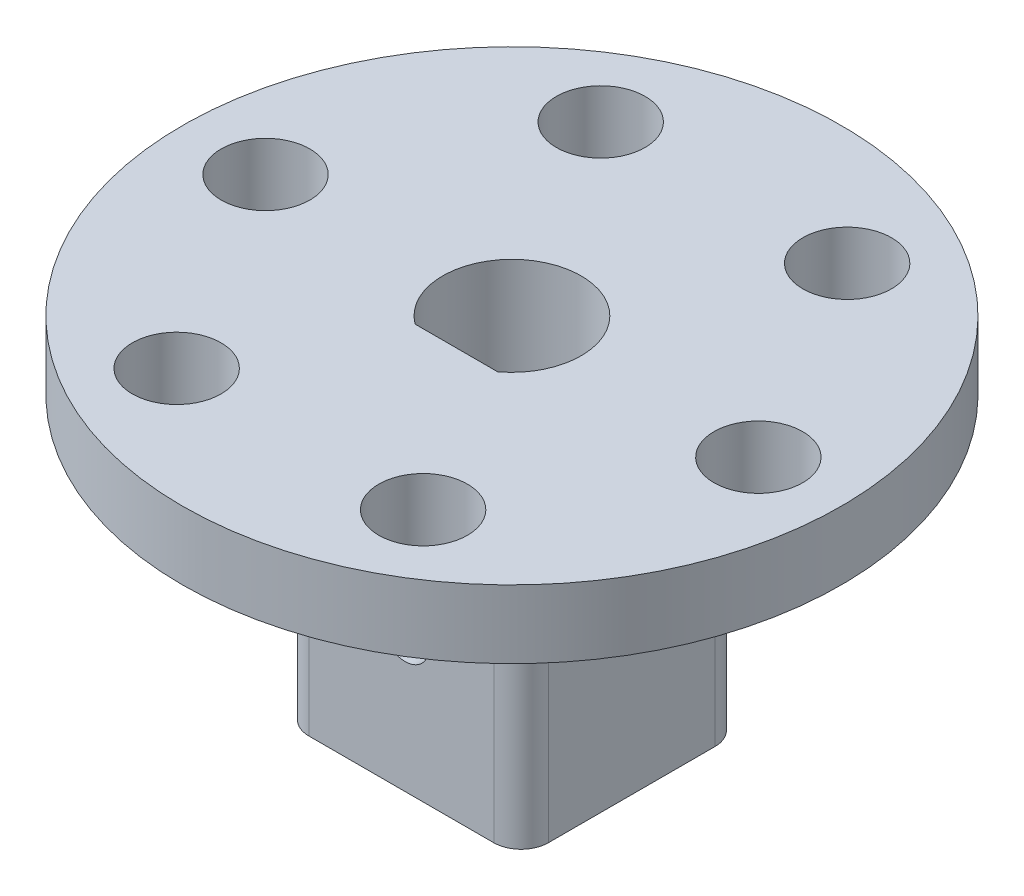
SolidWorks part; units mm, degrees
ref_plane "前视基准面" through (0, 0, 0) normal (0, 0, 1) x (1, 0, 0)
ref_plane "上视基准面" through (0, 0, 0) normal (0, 1, 0) x (1, 0, 0)
ref_plane "右视基准面" through (0, 0, 0) normal (1, 0, 0) x (0, 0, -1)
sketch "草图1" plane through (0, 0, 0) normal (0, 1, 0) x (1, 0, 0)
  line L7 (-10.75, -10.75) -> (10.75, -10.75)
  line L8 (-10.75, -10.75) -> (-10.75, 10.75)
  line L9 (-10.75, 10.75) -> (10.75, 10.75)
  line L10 (10.75, -10.75) -> (10.75, 10.75)
  line L11 (-10.75, -10.75) -> (10.75, 10.75) construction
  line L12 (-10.75, 10.75) -> (10.75, -10.75) construction
  line L13 (-15, -15) -> (15, -15)
  line L14 (-15, -15) -> (-15, 15)
  line L15 (-15, 15) -> (15, 15)
  line L16 (15, -15) -> (15, 15)
  line L17 (-15, -15) -> (15, 15) construction
  line L18 (-15, 15) -> (15, -15) construction
  point P0 (0, 0)
  point P5 (0, 0)
  dimension "D1" = 21.5
  dimension "D2" = 21.5
  dimension "D3" = 30
  dimension "D4" = 30
extrude "凸台-拉伸1" add sketch "草图1" along normal blind 5
sketch "草图2" plane through (0, 5, 0) normal (0, 1, 0) x (1, 0, 0)
  line L1 (-15, 15) -> (15, 15)
  line L2 (-15, 15) -> (-15, -15)
  line L3 (-15, -15) -> (15, -15)
  line L4 (15, 15) -> (15, -15)
extrude "凸台-拉伸2" add sketch "草图2" along normal blind 5
sketch "草图3" plane through (0, 10, 0) normal (0, 1, 0) x (1, 0, 0)
  circle A0 centre (0, 0) radius 5.5
  dimension "D1" = 11
sketch "草图4" plane through (0, 10, 0) normal (0, 1, 0) x (1, 0, 0)
  line L6 (0, 0) -> (0, -3.7936) construction
  line L7 (-8.7773, 8.1079) -> (8.7773, 8.1079)
  line L8 (-8.7773, 8.1079) -> (-8.7773, -8.1079)
  line L9 (-8.7773, -8.1079) -> (8.7773, -8.1079)
  line L10 (8.7773, 8.1079) -> (8.7773, -8.1079)
  line L11 (0, 0) -> (3.9424, 0) construction
extrude "凸台-拉伸3" add sketch "草图4" along normal blind 11
sketch "草图5" plane through (0, 21, 0) normal (0, 1, 0) x (1, 0, 0)
  line L1 (8.9491, 15.6177) -> (-9.0508, 15.559) construction
  line L2 (-9.0508, 15.559) -> (-17.9999, -0.0587) construction
  line L3 (-17.9999, -0.0587) -> (-8.9491, -15.6177) construction
  line L4 (-8.9491, -15.6177) -> (9.0508, -15.559) construction
  line L5 (9.0508, -15.559) -> (17.9999, 0.0587) construction
  line L6 (17.9999, 0.0587) -> (8.9491, 15.6177) construction
  circle A0 centre (0, 0) radius 15.5885 construction
  circle A1 centre (8.9491, 15.6177) radius 3.25
  circle A2 centre (17.9999, 0.0587) radius 3.25
  circle A3 centre (9.0508, -15.559) radius 3.25
  circle A4 centre (-8.9491, -15.6177) radius 3.25
  circle A5 centre (-17.9999, -0.0587) radius 3.25
  circle A6 centre (-9.0508, 15.559) radius 3.25
  circle A7 centre (0, 0) radius 24.1522
  dimension "D2" = 6.5
  dimension "D1" = 18
  dimension "D3" = 6
extrude "凸台-拉伸4" add sketch "草图5" along normal blind 5
sketch "草图6" plane through (0, 5, 0) normal (0, -1, 0) x (1, 0, 0)
  line L0 (-3.0249, 4.075) -> (3.0249, 4.075)
  arc A0 (-3.0249, 4.075) -> (3.0249, 4.075) centre (0, 0) ccw
  point P1 (0, -5.075)
  dimension "D1" = 10.15
  dimension "D2" = 9.15
extrude "切除-拉伸2" cut sketch "草图6" against normal up to surface (21 mm away) up to face at (-17.9999, 26, 3.3087)
sketch "草图7" plane through (0, 5, 0) normal (0, -1, 0) x (1, 0, 0)
  circle A0 centre (0, 8.1351) radius 1.1
  circle A1 centre (0, -7.8649) radius 1.1
  dimension "D1" = 16
  dimension "D2" = 2.2
  dimension "D3" = 2.2
fillet "圆角1" radius 2 8 edges at (-8.7773, 15.5, -8.1079) (-8.7773, 15.5, 8.1079) (8.7773, 15.5, 8.1079) (8.7773, 15.5, -8.1079) (-15, 5, -15) (15, 5, -15) (-15, 5, 15) (15, 5, 15)
sketch "草图10" plane through (0, 5, 0) normal (0, -1, 0) x (1, 0, 0)
  line L4 (10.75, -10.75) -> (10.75, 10.75)
  line L6 (10.75, -10.75) -> (10.75, 10.75)
  line L12 (10.75, 10.75) -> (-10.75, 10.75)
  line L14 (10.75, 10.75) -> (-10.75, 10.75)
  line L16 (-10.75, 10.75) -> (-10.75, -10.75)
  line L17 (-10.75, 10.75) -> (-10.75, -10.75)
  line L18 (-10.75, -10.75) -> (10.75, -10.75)
  line L19 (-10.75, -10.75) -> (10.75, -10.75)
  dimension "D1" = 0
extrude "凸台-拉伸5" add sketch "草图10" along normal up to surface (5 mm away) up to face at (0, 0, 0)
sketch "草图11" plane through (0, 0, 8.1079) normal (0, 0, 1) x (1, 0, 0)
  line L0 (5.5, 10) -> (-5.5, 10) construction
  circle A0 centre (0.2776, 10) radius 1.75
  dimension "D1" = 3.5
extrude "切除-拉伸3" cut sketch "草图11" against normal up to surface and the other way up to next up to face at (0, 5, -15)
sketch "草图12" plane through (0, 21, 0) normal (0, -1, 0) x (1, 0, 0)
  line L0 (-8.7773, -6.1079) -> (-8.7773, 6.1079) construction
  line L1 (6.7773, -8.1079) -> (-6.7773, -8.1079) construction
  line L2 (8.7773, 6.1079) -> (8.7773, -6.1079) construction
  line L3 (-6.7773, 8.1079) -> (6.7773, 8.1079) construction
  line L4 (-8.7773, -6.1079) -> (-8.7773, 6.1079)
  line L5 (6.7773, -8.1079) -> (-6.7773, -8.1079)
  line L6 (8.7773, 6.1079) -> (8.7773, -6.1079)
  line L7 (-6.7773, 8.1079) -> (6.7773, 8.1079)
  arc A0 (-8.7773, -6.1079) -> (-6.7773, -8.1079) centre (-6.7773, -6.1079) ccw construction
  circle A1 centre (0, 0) radius 24.1522 construction
  arc A3 (6.7773, -8.1079) -> (8.7773, -6.1079) centre (6.7773, -6.1079) ccw construction
  arc A4 (8.7773, 6.1079) -> (6.7773, 8.1079) centre (6.7773, 6.1079) ccw construction
  arc A5 (-6.7773, 8.1079) -> (-8.7773, 6.1079) centre (-6.7773, 6.1079) ccw construction
  arc A6 (-8.7773, -6.1079) -> (-6.7773, -8.1079) centre (-6.7773, -6.1079) ccw
  arc A7 (6.7773, -8.1079) -> (8.7773, -6.1079) centre (6.7773, -6.1079) ccw
  arc A8 (8.7773, 6.1079) -> (6.7773, 8.1079) centre (6.7773, 6.1079) ccw
  arc A9 (-6.7773, 8.1079) -> (-8.7773, 6.1079) centre (-6.7773, 6.1079) ccw
  circle A10 centre (0, 0) radius 24.1522
extrude "切除-拉伸4" cut sketch "草图12" along normal up to surface (21 mm away) up to face at (0, 0, 0)
sketch "草图13" plane through (0, 5, 0) normal (0, 1, 0) x (1, 0, 0)
  line L1 (-3.0249, -4.075) -> (3.0249, -4.075)
  line L2 (-3.0249, -4.075) -> (3.0249, -4.075)
  arc A1 (3.0249, -4.075) -> (-3.0249, -4.075) centre (0, 0) ccw
  arc A2 (3.0249, -4.075) -> (-3.0249, -4.075) centre (0, 0) ccw
  dimension "D1" = 0
extrude "切除-拉伸5" cut sketch "草图13" against normal up to next
